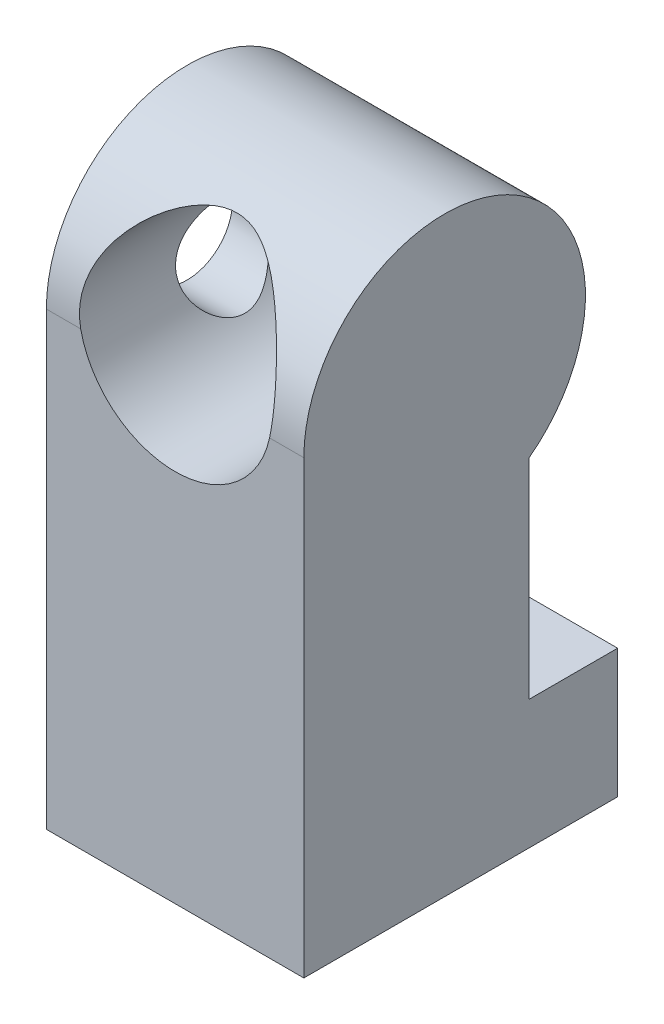
SolidWorks part; units mm, degrees
ref_plane "Front Plane" through (0, 0, 0) normal (0, 0, 1) x (1, 0, 0)
ref_plane "Top Plane" through (0, 0, 0) normal (0, 1, 0) x (1, 0, 0)
ref_plane "Right Plane" through (0, 0, 0) normal (1, 0, 0) x (0, 0, -1)
sketch "Sketch1" plane through (0, 0, 0) normal (1, 0, 0) x (0, 0, -1)
  line L0 (0, 0) -> (-7.8, 0)
  line L1 (-7.8, 0) -> (-7.8, 11.2)
  line L3 (-2.2, 8.4) -> (-2.2, 3.2)
  line L4 (-2.2, 3.2) -> (0, 3.2)
  line L5 (0, 3.2) -> (0, 0)
  arc A0 (-2.2, 8.4) -> (-7.8, 11.2) centre (-4.3, 11.2) ccw
  point P9 (-45.6345, 94.1027)
  point P10 (0, 0)
  point P11 (-20.8483, 84.902)
  point P12 (-21.0389, 84.7473)
  point P13 (-2.2, 5.8)
  dimension "D4" = 7
  dimension "D1" = 7.8
  dimension "D2" = 3.2
  dimension "D3" = 11.2
  dimension "D5" = 5.6
extrude "Boss-Extrude1" add sketch "Sketch1" along normal mid plane 6.4
sketch "Sketch2" plane through (0, 0, 0) normal (0, -1, 0) x (1, 0, 0)
  line L0 (3.2, 7.8) -> (-3.2, 7.8) construction
  line L1 (-2.4, 3.1) -> (2.4, 3.1)
  line L2 (-2.4, 3.1) -> (-2.4, 6.4)
  line L3 (-2.4, 6.4) -> (2.4, 6.4)
  line L4 (2.4, 3.1) -> (2.4, 6.4)
  line L5 (-2.4, 3.1) -> (2.4, 6.4) construction
  line L6 (-2.4, 6.4) -> (2.4, 3.1) construction
  line L7 (0, -14.4891) -> (0, 87.038) construction
  point P0 (0, 4.75)
  point P10 (0, 87.038)
  point P11 (0, 0)
  dimension "D1" = 4.8
  dimension "D2" = 3.3
  dimension "D3" = 1.4
extrude "Cut-Extrude1" cut sketch "Sketch2" against normal blind 8.9
sketch "Sketch3" plane through (-3.2, 0, 0) normal (-1, 0, 0) x (0, 0, 1)
  line L0 (121.6998, 11.2) -> (-44.4703, 11.2) construction
  line L1 (4.3, 11.2) -> (4.3, -17.5469) construction
  line L2 (4.3, 11.2) -> (4.3, 161.2081) construction
  circle A0 centre (4.3, 11.2) radius 1.125
  dimension "D1" = 2.25
extrude "Cut-Extrude2" cut sketch "Sketch3" against normal blind 2
sketch "Sketch4" plane through (0, 0, 7.8) normal (0, 0, 1) x (1, 0, 0)
  line L0 (0, -27.3065) -> (0, 165.831) construction
  line L1 (-66.7763, 11.7) -> (74.2244, 11.7) construction
  line L2 (3.2, 0) -> (-3.2, 0) construction
  circle A0 centre (0, 11.7) radius 2.4
  point P9 (0, 0)
  dimension "D2" = 4.8
  dimension "D1" = 11.7
extrude "Cut-Extrude3" cut sketch "Sketch4" against normal blind 5
